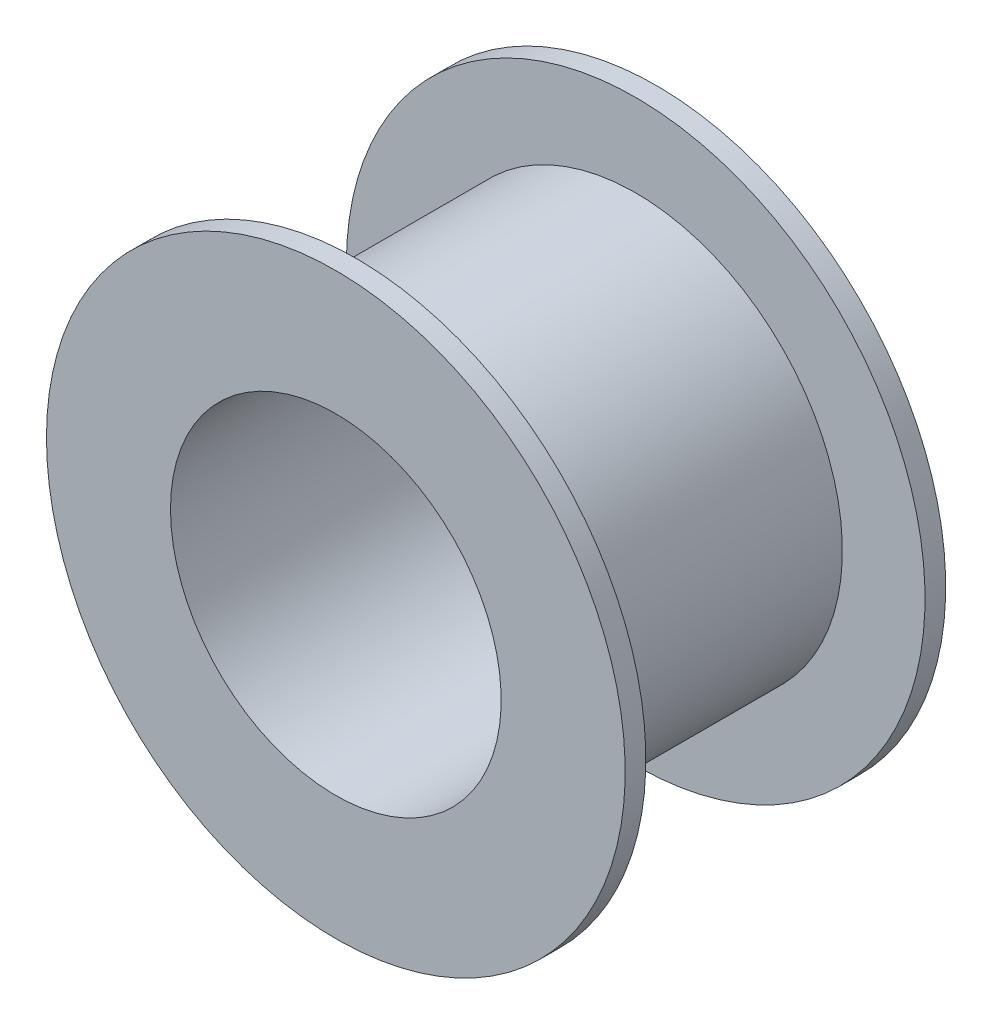
SolidWorks part; units mm, degrees
ref_plane "Front Plane" through (0, 0, 0) normal (1, 0, 0) x (0, 1, 0)
ref_plane "Top Plane" through (0, 0, 0) normal (0, 0, 1) x (0, 1, 0)
ref_plane "Right Plane" through (0, 0, 0) normal (0, 1, 0) x (-1, 0, 0)
sketch "Sketch2" plane through (0, 0, 0) normal (1, 0, 0) x (0, 1, 0)
  line L0 (-50.8, 0) -> (-88.9, 0)
  line L6 (-88.9, 98.4738) -> (-50.8, 98.4738)
  line L7 (-50.8, 98.4738) -> (-50.8, 0)
  line L8 (0, 0) -> (0, 98.4738) construction
  line L9 (-88.9, 98.4738) -> (-88.9, 92.1238)
  line L10 (-88.9, 92.1238) -> (-63.5, 92.1238)
  line L11 (-63.5, 92.1238) -> (-63.5, 6.35)
  line L12 (-63.5, 6.35) -> (-88.9, 6.35)
  line L13 (-88.9, 6.35) -> (-88.9, 0)
  point P3 (0, 0)
  dimension "D1" = 50.8
  dimension "D2" = 88.9
  dimension "D3" = 63.5
  dimension "D4" = 88.9
  dimension "D5" = 6.35
  dimension "D6" = 6.35
revolve "Revolve1" add sketch "Sketch2" angle 360 about L8
